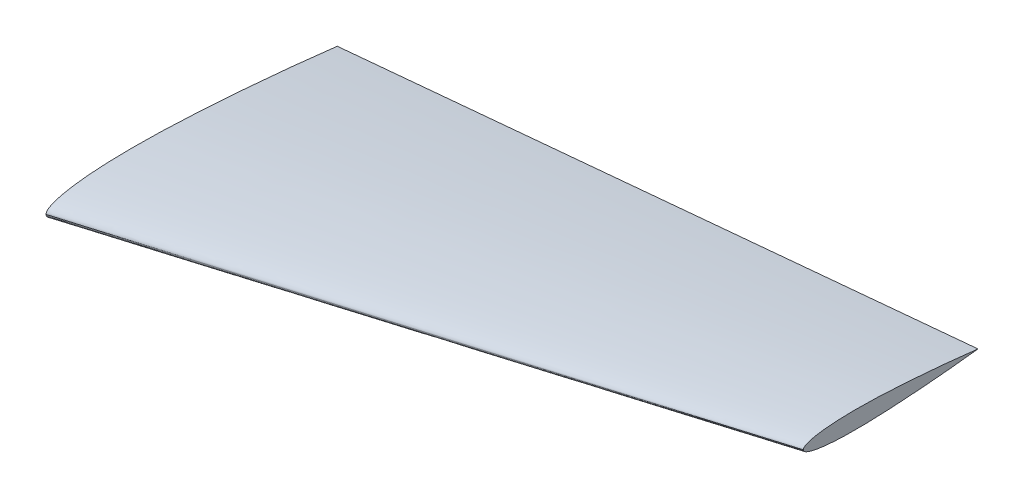
SolidWorks part; units mm, degrees
ref_plane "Front Plane" through (0, 0, 0) normal (0, 0, 1) x (1, 0, 0)
ref_plane "Top Plane" through (0, 0, 0) normal (0, 1, 0) x (1, 0, 0)
ref_plane "Right Plane" through (0, 0, 0) normal (1, 0, 0) x (0, 0, -1)
sketch "0010 template"
sketch_block_instance "Block2-1"
sketch_block "Block2"
sketch "Sketch4" plane through (0, 0, 0) normal (1, 0, 0) x (0, 0, -1)
  line L0 (0, 0) -> (-250, 0) construction
  spline S0 degree 4 poles (-250, 0) (-249.9999, 0.1958) (-249.9612, 0.6039) (-249.7596, 1.2633) (-249.1282, 2.2398) (-248.1098, 3.1752) (-246.5761, 4.1828) (-244.1271, 5.3667) (-240.0739, 6.8179) (-232.84, 8.6113) (-221.2945, 10.4497) (-205.8077, 11.8178) (-187.4923, 12.5325) (-167.6157, 12.5624) (-147.9613, 12.1042) (-127.9831, 11.2209) (-108.5655, 10.1073) (-88.2725, 8.6479) (-69.4578, 7.1641) (-48.2492, 5.205) (-31.0441, 3.5474) (-5.6278, 0.7144) (5.3818, -0.6305) (19.3913, -2.4508) (24.9342, -3.2323) knots 0 0 0 0 0 0.002791 0.005883 0.009735 0.016522 0.022438 0.032158 0.048634 0.078249 0.129037 0.199997 0.270957 0.341918 0.412878 0.483838 0.554798 0.625759 0.696719 0.767679 0.83864 0.9096 1 1 1 1 1 construction
  spline S1 degree 4 poles (-250, 0) (-249.9999, 0.1958) (-249.9612, 0.6039) (-249.7596, 1.2633) (-249.1282, 2.2398) (-248.1098, 3.1752) (-246.5761, 4.1828) (-244.1271, 5.3667) (-240.0739, 6.8179) (-232.84, 8.6113) (-221.2945, 10.4497) (-205.8077, 11.8178) (-187.4923, 12.5325) (-167.6157, 12.5624) (-147.9613, 12.1042) (-127.9831, 11.2209) (-108.5655, 10.1073) (-88.2725, 8.6479) (-69.4578, 7.1641) (-48.2492, 5.205) (-31.0441, 3.5474) (-13.2038, 1.5588) (-4.4672, 0.5411) (0, 0) knots 0 0 0 0 0 0.002791 0.005883 0.009735 0.016522 0.022438 0.032158 0.048634 0.078249 0.129037 0.199997 0.270957 0.341918 0.412878 0.483838 0.554798 0.625759 0.696719 0.767679 0.83864 0.9096 0.9096 0.9096 0.9096 0.9096
  spline S2 degree 4 poles (-250, 0) (-249.9999, -0.1958) (-249.9612, -0.6039) (-249.7596, -1.2633) (-249.1282, -2.2398) (-248.1098, -3.1752) (-246.5761, -4.1828) (-244.1271, -5.3667) (-240.0739, -6.8179) (-232.84, -8.6113) (-221.2945, -10.4497) (-205.8077, -11.8178) (-187.4923, -12.5325) (-167.6157, -12.5624) (-147.9613, -12.1042) (-127.9831, -11.2209) (-108.5655, -10.1073) (-88.2725, -8.6479) (-69.4578, -7.1641) (-48.2492, -5.205) (-31.0441, -3.5474) (-13.2038, -1.5588) (-4.4672, -0.5411) (0, 0) knots 0 0 0 0 0 0.002791 0.005883 0.009735 0.016522 0.022438 0.032158 0.048634 0.078249 0.129037 0.199997 0.270957 0.341918 0.412878 0.483838 0.554798 0.625759 0.696719 0.767679 0.83864 0.9096 0.9096 0.9096 0.9096 0.9096
ref_plane "Plane1" through (500, 0, 0) normal (1, 0, 0) x (0, 0, -1)
sketch "Sketch7" plane through (500, 0, 0) normal (1, 0, 0) x (0, 0, -1)
  line L0 (50, 0) -> (-100, 0) construction
  spline S0 degree 4 poles (-100, 0) (-99.9999, 0.1175) (-99.9767, 0.3624) (-99.8557, 0.758) (-99.4769, 1.3439) (-98.8659, 1.9051) (-97.9457, 2.5097) (-96.4763, 3.22) (-94.0443, 4.0908) (-89.704, 5.1668) (-82.7767, 6.2698) (-73.4846, 7.0907) (-62.4954, 7.5195) (-50.5694, 7.5374) (-38.7768, 7.2625) (-26.7899, 6.7325) (-15.1393, 6.0644) (-2.9635, 5.1887) (8.3253, 4.2985) (21.0505, 3.123) (31.3735, 2.1284) (46.6233, 0.4286) (53.2291, -0.3783) (61.6348, -1.4705) (64.9605, -1.9394) knots 0 0 0 0 0 0.002791 0.005883 0.009735 0.016522 0.022438 0.032158 0.048634 0.078249 0.129037 0.199997 0.270957 0.341918 0.412878 0.483838 0.554798 0.625759 0.696719 0.767679 0.83864 0.9096 1 1 1 1 1 construction
  spline S1 degree 4 poles (-100, 0) (-99.9999, 0.1175) (-99.9767, 0.3624) (-99.8557, 0.758) (-99.4769, 1.3439) (-98.8659, 1.9051) (-97.9457, 2.5097) (-96.4763, 3.22) (-94.0443, 4.0908) (-89.704, 5.1668) (-82.7767, 6.2698) (-73.4846, 7.0907) (-62.4954, 7.5195) (-50.5694, 7.5374) (-38.7768, 7.2625) (-26.7899, 6.7325) (-15.1393, 6.0644) (-2.9635, 5.1887) (8.3253, 4.2985) (21.0505, 3.123) (31.3735, 2.1284) (42.0777, 0.9353) (47.3197, 0.3247) (50, 0) knots 0 0 0 0 0 0.002791 0.005883 0.009735 0.016522 0.022438 0.032158 0.048634 0.078249 0.129037 0.199997 0.270957 0.341918 0.412878 0.483838 0.554798 0.625759 0.696719 0.767679 0.83864 0.9096 0.9096 0.9096 0.9096 0.9096
  spline S2 degree 4 poles (-100, 0) (-99.9999, -0.1175) (-99.9767, -0.3624) (-99.8557, -0.758) (-99.4769, -1.3439) (-98.8659, -1.9051) (-97.9457, -2.5097) (-96.4763, -3.22) (-94.0443, -4.0908) (-89.704, -5.1668) (-82.7767, -6.2698) (-73.4846, -7.0907) (-62.4954, -7.5195) (-50.5694, -7.5374) (-38.7768, -7.2625) (-26.7899, -6.7325) (-15.1393, -6.0644) (-2.9635, -5.1887) (8.3253, -4.2985) (21.0505, -3.123) (31.3735, -2.1284) (42.0777, -0.9353) (47.3197, -0.3247) (50, 0) knots 0 0 0 0 0 0.002791 0.005883 0.009735 0.016522 0.022438 0.032158 0.048634 0.078249 0.129037 0.199997 0.270957 0.341918 0.412878 0.483838 0.554798 0.625759 0.696719 0.767679 0.83864 0.9096 0.9096 0.9096 0.9096 0.9096
  point P5 (0, 0)
  point P6 (-173.4038, -1.179)
  point P7 (-12.005, -79.6175)
  point P8 (-173.7521, 8.9028)
  dimension "D1" = 50
loft "Loft2" add profiles "Sketch7", "Sketch4"
